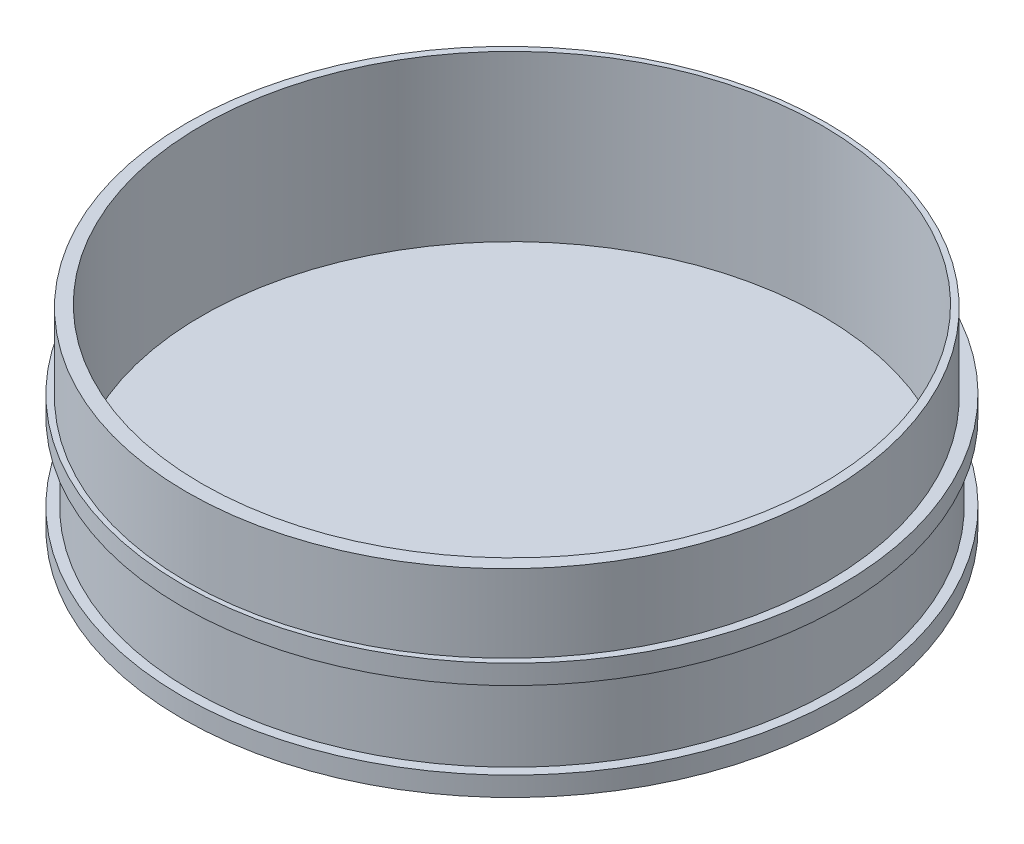
SolidWorks part; units mm, degrees
ref_plane "前视基准面" through (0, 0, 0) normal (0, 0, 1) x (1, 0, 0)
ref_plane "上视基准面" through (0, 0, 0) normal (0, 1, 0) x (1, 0, 0)
ref_plane "右视基准面" through (0, 0, 0) normal (1, 0, 0) x (0, 0, -1)
sketch "草图1" plane through (0, 0, 0) normal (0, 1, 0) x (1, 0, 0)
  circle A0 centre (0, 0) radius 17
  dimension "D1" = 34
extrude "凸台-拉伸1" add sketch "草图1" along normal blind 1
sketch "草图2" plane through (0, 1, 0) normal (0, 1, 0) x (1, 0, 0)
  circle A0 centre (0, 0) radius 16.5
  dimension "D1" = 33
extrude "凸台-拉伸2" add sketch "草图2" along normal blind 4
sketch "草图3" plane through (0, 5, 0) normal (0, 1, 0) x (1, 0, 0)
  circle A0 centre (0, 0) radius 17
  dimension "D1" = 34
extrude "凸台-拉伸3" add sketch "草图3" along normal blind 1
sketch "草图4" plane through (0, 6, 0) normal (0, 1, 0) x (1, 0, 0)
  circle A0 centre (0, -0.2632) radius 16.5
  dimension "D1" = 33
extrude "凸台-拉伸4" add sketch "草图4" along normal blind 4
sketch "草图5" plane through (0, 10, 0) normal (0, 1, 0) x (1, 0, 0)
  circle A0 centre (0, 0) radius 16
  dimension "D1" = 32
extrude "切除-拉伸1" cut sketch "草图5" against normal blind 8.5
